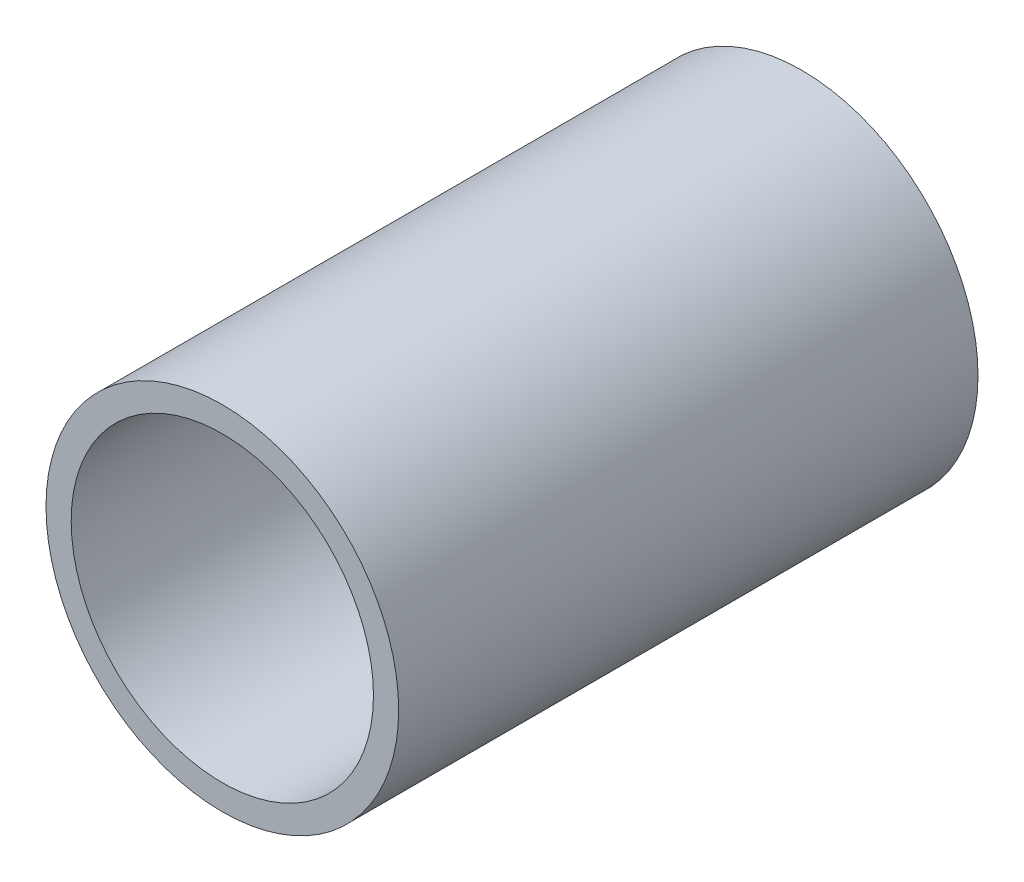
SolidWorks part; units mm, degrees
ref_plane "Front Plane" through (0, 0, 0) normal (0, 0, 1) x (1, 0, 0)
ref_plane "Top Plane" through (0, 0, 0) normal (0, 1, 0) x (1, 0, 0)
ref_plane "Right Plane" through (0, 0, 0) normal (1, 0, 0) x (0, 0, -1)
sketch "Sketch1" plane through (0, 0, 0) normal (0, 0, 1) x (1, 0, 0)
  line L4 (-22.225, 0) -> (-19.05, 0) construction
  circle A0 centre (0, 0) radius 22.225
  circle A1 centre (0, 0) radius 19.05
  dimension "OD" = 44.45
  dimension "ID" = 38.1
sketch "Sketch2" plane through (0, 0, 0) normal (1, 0, 0) x (0, 0, -1)
  line L0 (-914.4, 22.225) -> (914.4, 22.225) construction
  point P2 (0, 22.225)
  point P3 (-869.95, 22.225)
  point P5 (869.95, 22.225)
  dimension "Length" = 1828.8
  dimension "D1" = 44.45
  dimension "D2" = 44.45
extrude "Boss-Extrude1" add sketch "Sketch1" along normal up to vertex (914.4 mm away) and the other way up to vertex (914.4 mm away) up to point (0, 22.225, 914.4) other way up to point (0, 22.225, -914.4)
sketch "Sketch3" plane through (0, 0, 914.4) normal (0, 0, 1) x (1, 0, 0)
  circle A1 centre (0, 0) radius 22.225
  circle A2 centre (0, 0) radius 22.225
  dimension "D1" = 0
extrude "Cut-Extrude1" cut sketch "Sketch3" against normal offset from surface (1755.775 mm away) 73.025 up to face at (19.05, 0, -914.4)
equation "\"D1@Sketch2\"=\"OD@Sketch1\""
equation "\"D2@Sketch2\"=\"D1@Sketch2\""
